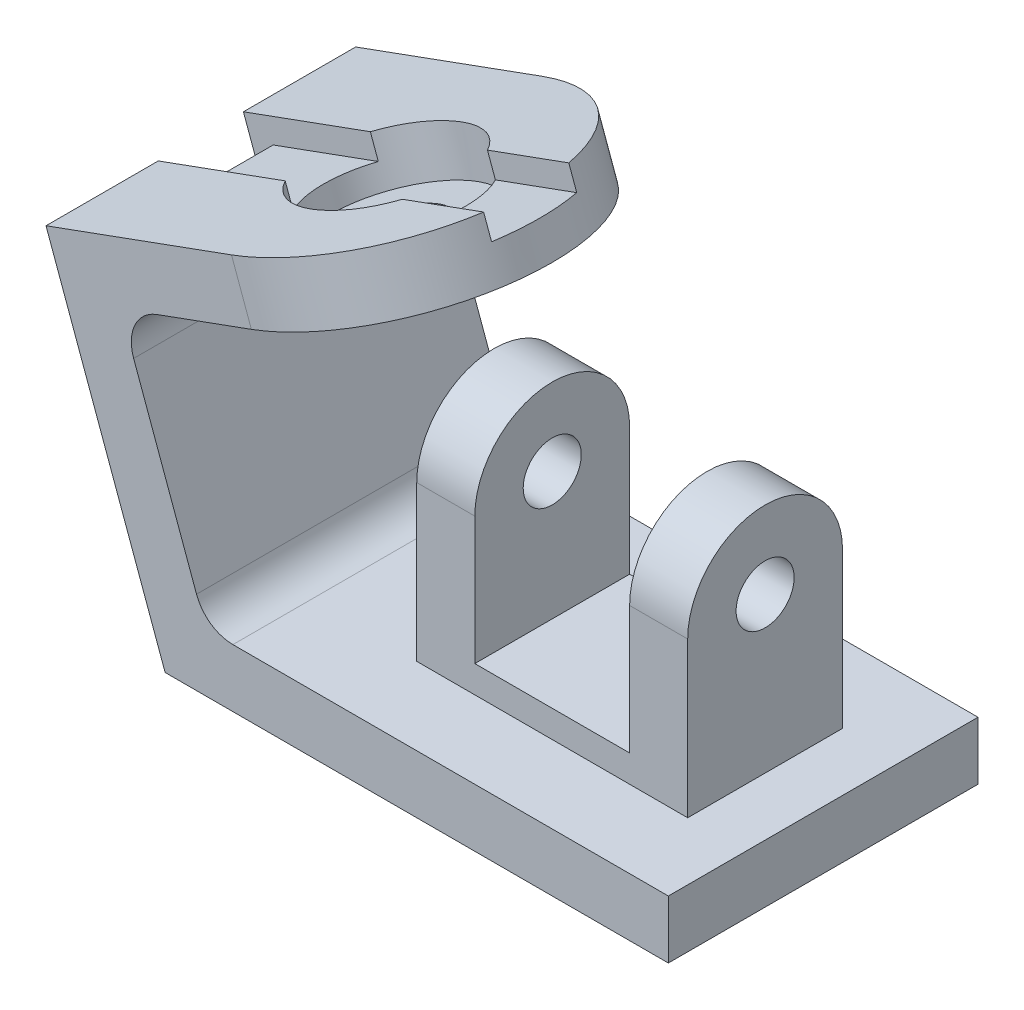
SolidWorks part; units mm, degrees
material "Laiton"
ref_plane "Plan de face" through (0, 0, 0) normal (0, 0, 1) x (1, 0, 0)
ref_plane "Plan de dessus" through (0, 0, 0) normal (0, 1, 0) x (1, 0, 0)
ref_plane "Plan de droite" through (0, 0, 0) normal (1, 0, 0) x (0, 0, -1)
sketch "Esquisse1" plane through (0, 0, 0) normal (0, 0, 1) x (1, 0, 0)
  line L0 (0, 0) -> (130, 0) construction
  line L1 (0, 0) -> (-30.7818, 84.5723)
  line L2 (-30.7818, 84.5723) -> (17.1425, 102.0154)
  line L3 (17.1425, 102.0154) -> (22.2728, 87.92)
  line L4 (22.2728, 87.92) -> (-11.5561, 75.6072)
  line L5 (-11.5561, 75.6072) -> (10.5031, 15)
  line L6 (10.5031, 15) -> (130, 15)
  line L7 (130, 15) -> (130, 0)
  line L8 (130, 0) -> (0, 0)
  dimension "D1" = 130
  dimension "D2" = 70
  dimension "D3" = 15
  dimension "D4" = 15
  dimension "D5" = 15
  dimension "D6" = 90
  dimension "D7" = 51
extrude "Boss.-Extru.1" add sketch "Esquisse1" against normal blind 80
sketch "Esquisse2" plane through (-30.7818, 84.5723, 0) normal (-0.342, 0.9397, 0) x (0.9397, 0.342, 0)
  line L0 (127.2903, 0) -> (15, 0) construction
  line L1 (51, 80) -> (51, 0)
  arc A0 (51, 80) -> (51, 0) centre (51, 40) cw
  dimension "D1" = 40
extrude "Boss.-Extru.2" add sketch "Esquisse2" against normal blind 15
sketch "Esquisse3" plane through (-30.7818, 84.5723, 0) normal (-0.342, 0.9397, 0) x (0.9397, 0.342, 0)
  circle A0 centre (51, 40) radius 9.5
  dimension "D1" = 19
extrude "Enlèv. mat.-Extru.1" cut sketch "Esquisse3" against normal up to next
sketch "Esquisse4" plane through (-30.7818, 84.5723, 0) normal (-0.342, 0.9397, 0) x (0.9397, 0.342, 0)
  line L0 (0, 40) -> (95.651, 40) construction
  line L1 (0, 80) -> (0, 0) construction
  line L3 (0, 51) -> (89.4578, 51)
  line L4 (0, 51) -> (0, 29)
  line L5 (0, 29) -> (89.4578, 29)
  line L7 (0, 51) -> (89.4578, 29) construction
  line L8 (0, 29) -> (89.4578, 51) construction
  arc A0 (51, 0) -> (51, 80) centre (51, 40) ccw construction
  arc A1 (89.4578, 29) -> (89.4578, 51) centre (51, 40) ccw
  point P4 (44.7289, 40)
  dimension "D1" = 22
extrude "Enlèv. mat.-Extru.2" cut sketch "Esquisse4" against normal blind 6
sketch "Esquisse5" plane through (-30.7818, 84.5723, 0) normal (-0.342, 0.9397, 0) x (0.9397, 0.342, 0)
  circle A0 centre (51, 40) radius 19.5
  dimension "D1" = 39
extrude "Enlèv. mat.-Extru.3" cut sketch "Esquisse5" against normal blind 12
sketch "Esquisse6" plane through (0, 0, 0) normal (-0.9397, -0.342, 0) x (0, 0, 1)
  line L0 (-40, 0) -> (-40, 107.7621) construction
  line L1 (-80, 0) -> (0, 0) construction
  line L3 (-51, 90) -> (-29, 90)
  line L4 (-51, 90) -> (-51, 34)
  line L5 (-51, 34) -> (-29, 34)
  line L6 (-29, 90) -> (-29, 34)
  line L7 (-51, 90) -> (-29, 34) construction
  line L8 (-51, 34) -> (-29, 90) construction
  point P4 (-40, 62)
  dimension "D1" = 56
extrude "Enlèv. mat.-Extru.4" cut sketch "Esquisse6" against normal blind 6
ref_plane "Plan2" through (115, 0, 0) normal (1, 0, 0) x (0, 0, -1)
sketch "Esquisse8" plane through (115, 0, 0) normal (1, 0, 0) x (0, 0, -1)
  line L0 (20, 15) -> (20, 55)
  line L1 (80, 15) -> (0, 15) construction
  line L2 (60, 55) -> (60, 15)
  line L3 (60, 15) -> (20, 15)
  line L4 (0, 0) -> (0, 15) construction
  arc A0 (20, 55) -> (60, 55) centre (40, 55) cw
  point P6 (40, 15)
  dimension "D1" = 40
  dimension "D2" = 40
  dimension "D3" = 40
extrude "Boss.-Extru.3" add sketch "Esquisse8" against normal blind 70
sketch "Esquisse9" plane through (0, 0, -20) normal (0, 0, 1) x (1, 0, 0)
  line L0 (115, 75) -> (45, 75) construction
  line L1 (60, 22) -> (100, 22)
  line L2 (60, 22) -> (60, 75)
  line L3 (60, 75) -> (100, 75)
  line L4 (100, 22) -> (100, 75)
  line L5 (80, 15) -> (80, 76.7556) construction
  line L6 (45, 15) -> (115, 15) construction
  dimension "D1" = 40
  dimension "D2" = 7
extrude "Enlèv. mat.-Extru.5" cut sketch "Esquisse9" against normal through all
sketch "Esquisse10" plane through (45, 0, 0) normal (-1, 0, 0) x (0, 0, 1)
  circle A0 centre (-40, 55) radius 7.5
  dimension "D1" = 15
extrude "Enlèv. mat.-Extru.6" cut sketch "Esquisse10" against normal through all
fillet "Congé1" radius 10 2 edges at (-11.5561, 75.6072, -40) (10.5031, 15, -40)
equation "\"A\" = 70deg"
equation "\"B\" = 80"
equation "\"C\" = 130"
equation "\"D\" = 15"
equation "\"D1@Esquisse1\"=\"C\""
equation "\"D2@Esquisse1\"=\"A\""
equation "\"D3@Esquisse1\"=\"D\""
equation "\"D4@Esquisse1\"=\"D\""
equation "\"D5@Esquisse1\"=\"D\""
equation "\"D1@Boss.-Extru.1\"=\"B\""
equation "\"D1@Esquisse2\"=\"B\" / 2"
equation "\"D1@Boss.-Extru.2\"=\"D\""
equation "\"D1@Esquisse8\"=\"B\" / 2"
equation "\"E\"= 40"
equation "\"D2@Esquisse8\"=\"E\""
equation "\"D3@Esquisse8\"=\"E\""
